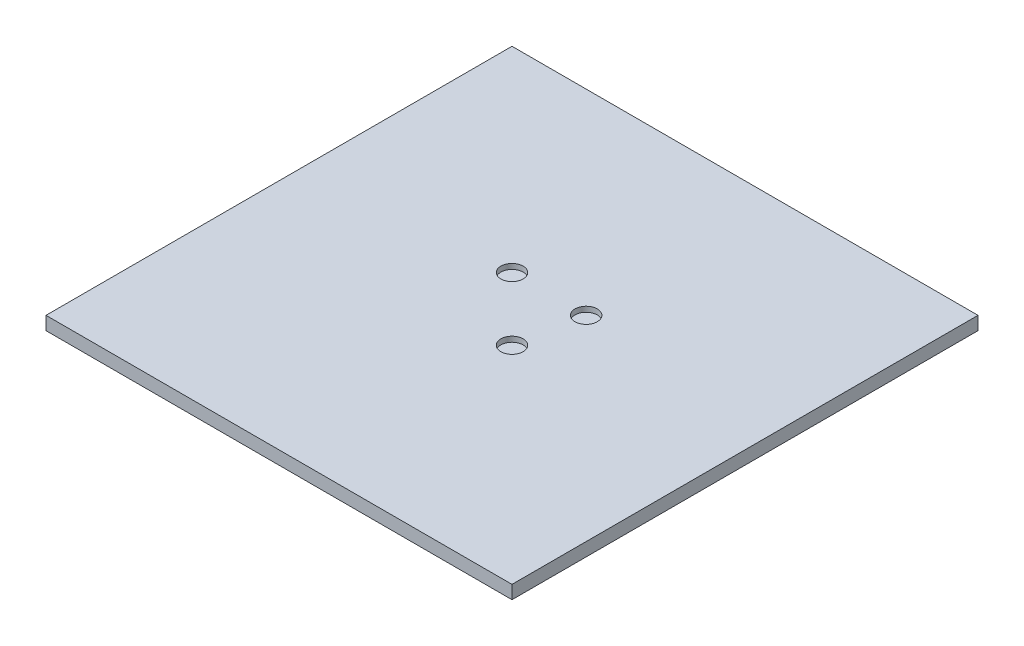
SolidWorks part; units mm, degrees
ref_plane "Front Plane" through (0, 0, 0) normal (0, 0, 1) x (1, 0, 0)
ref_plane "Top Plane" through (0, 0, 0) normal (0, 1, 0) x (1, 0, 0)
ref_plane "Right Plane" through (0, 0, 0) normal (1, 0, 0) x (0, 0, -1)
sketch "Sketch1" plane through (0, 0, 0) normal (0, 1, 0) x (1, 0, 0)
  line L1 (-44.45, -44.45) -> (44.45, -44.45)
  line L2 (-44.45, -44.45) -> (-44.45, 44.45)
  line L3 (-44.45, 44.45) -> (44.45, 44.45)
  line L4 (44.45, -44.45) -> (44.45, 44.45)
  line L5 (-44.45, -44.45) -> (44.45, 44.45) construction
  line L6 (-44.45, 44.45) -> (44.45, -44.45) construction
  point P0 (0, 0)
  dimension "D1" = 88.9
  dimension "D2" = 88.9
extrude "Boss-Extrude1" add sketch "Sketch1" along normal blind 2.54
sketch "Sketch2" plane through (0, 2.54, 0) normal (0, 1, 0) x (1, 0, 0)
  line L0 (0, 44.45) -> (0, -44.45) construction
  line L1 (0, -3.3588) -> (3.3588, 0)
  line L2 (0, -3.3588) -> (-3.3588, 0)
  line L3 (-3.3588, 0) -> (0, 3.3588)
  line L4 (3.3588, 0) -> (0, 3.3588)
  line L5 (0, -3.3588) -> (0, 3.3588) construction
  line L6 (-3.3588, 0) -> (3.3588, 0) construction
  line L7 (44.45, 44.45) -> (-44.45, 44.45) construction
  line L8 (-44.45, -44.45) -> (44.45, -44.45) construction
  point P0 (0, 0)
  dimension "D1" = 4.75
extrude "Boss-Extrude2" [suppressed] add sketch "Sketch2" along normal blind 5
sketch "Sketch3" plane through (0, 2.54, 0) normal (0, 1, 0) x (1, 0, 0)
  line L0 (-44.45, 44.45) -> (44.45, -44.45) construction
  line L1 (44.45, 44.45) -> (-44.45, -44.45) construction
  line L2 (0, 0) -> (7.0711, 7.0711)
  line L3 (0, 0) -> (4.9497, -4.9497)
  line L4 (0, 0) -> (-7.0711, 7.0711)
  circle A0 centre (-7.0711, 7.0711) radius 2.125
  circle A1 centre (7.0711, 7.0711) radius 2.125
  circle A2 centre (4.9497, -4.9497) radius 2.125
  dimension "D2" = 7
  dimension "D4" = 4.25
  dimension "D1" = 10
  dimension "D3" = 10
extrude "Cut-Extrude1" cut sketch "Sketch3" against normal blind 1
